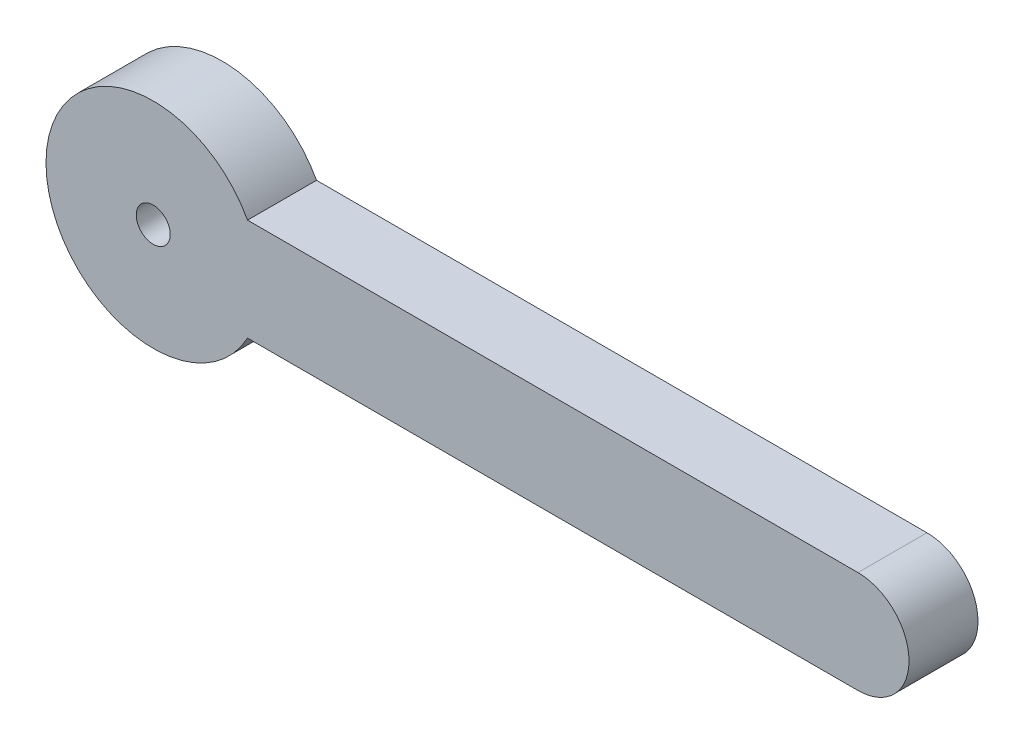
SolidWorks part; units mm, degrees
ref_plane "前视基准面" through (0, 0, 0) normal (0, 0, 1) x (1, 0, 0)
ref_plane "上视基准面" through (0, 0, 0) normal (0, 1, 0) x (1, 0, 0)
ref_plane "右视基准面" through (0, 0, 0) normal (1, 0, 0) x (0, 0, -1)
other "Configuration Table"
sketch "草图1" plane through (0, 0, 0) normal (0, 0, 1) x (1, 0, 0)
  line L0 (15.5467, 0) -> (102.1631, 0) construction
  line L1 (0, -7.4045) -> (0, 0)
  line L2 (13.6702, 7.4045) -> (102.1631, 7.4045)
  line L3 (13.6702, -7.4045) -> (102.1631, -7.4045)
  arc A0 (13.6702, 7.4045) -> (13.6702, -7.4045) centre (0, 0) ccw
  arc A1 (102.1631, 7.4045) -> (102.1631, -7.4045) centre (102.1631, 0) cw
extrude "凸台-拉伸1" add sketch "草图1" along normal blind 10
sketch "草图2" plane through (0, 0, 0) normal (0, 0, -1) x (-1, 0, 0)
  circle A0 centre (0, 0) radius 8.1202
extrude "切除-拉伸1" cut sketch "草图2" against normal blind 5 and the other way through all
sketch "草图3" plane through (0, 0, 10) normal (0, 0, 1) x (1, 0, 0)
  circle A0 centre (0, 0) radius 2.4668
extrude "切除-拉伸2" cut sketch "草图3" against normal blind 5
